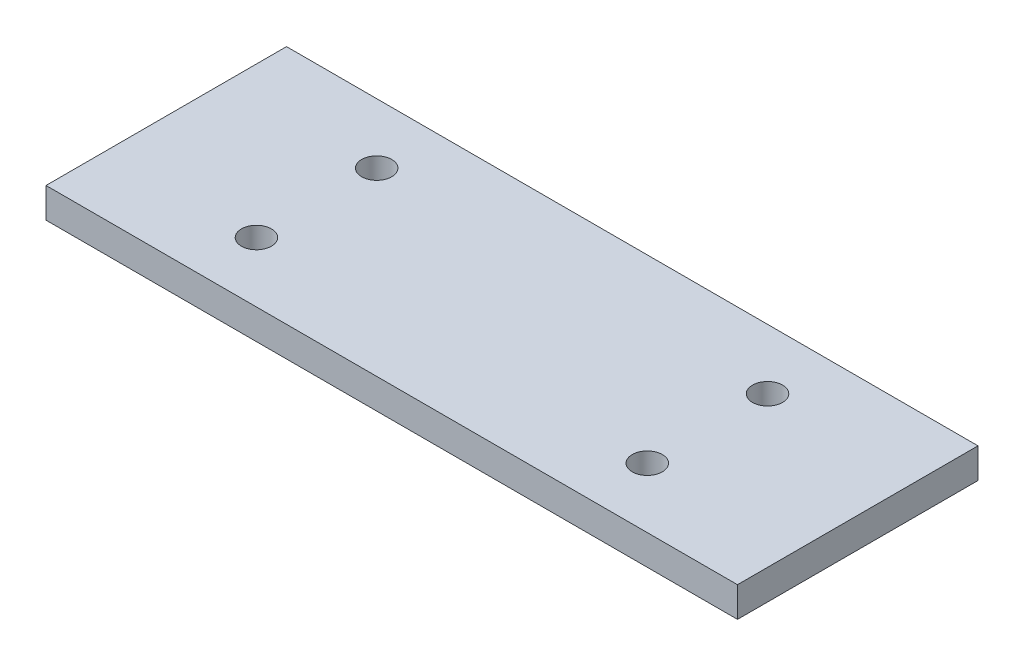
SolidWorks part; units mm, degrees
ref_plane "Front Plane" through (0, 0, 0) normal (0, 0, 1) x (1, 0, 0)
ref_plane "Top Plane" through (0, 0, 0) normal (0, 1, 0) x (1, 0, 0)
ref_plane "Right Plane" through (0, 0, 0) normal (1, 0, 0) x (0, 0, -1)
sketch "Sketch1" plane through (0, 0, 0) normal (0, 1, 0) x (1, 0, 0)
  line L0 (0, 14.7486) -> (0, 0) construction
  line L1 (-57.5, -20) -> (57.5, -20)
  line L2 (-57.5, -20) -> (-57.5, 20)
  line L3 (-57.5, 20) -> (57.5, 20)
  line L4 (57.5, -20) -> (57.5, 20)
  line L5 (-57.5, -20) -> (57.5, 20) construction
  line L6 (-57.5, 20) -> (57.5, -20) construction
  line L7 (0, 0) -> (42.6655, 0) construction
  circle A0 centre (32.5, 10) radius 2.5
  circle A1 centre (32.5, -10) radius 2.5
  circle A2 centre (-32.5, -10) radius 2.5
  circle A3 centre (-32.5, 10) radius 2.5
  point P0 (0, 0)
  dimension "D3" = 5
  dimension "D1" = 115
  dimension "D2" = 40
  dimension "D4" = 25
  dimension "D5" = 10
extrude "Boss-Extrude1" add sketch "Sketch1" along normal mid plane 5
